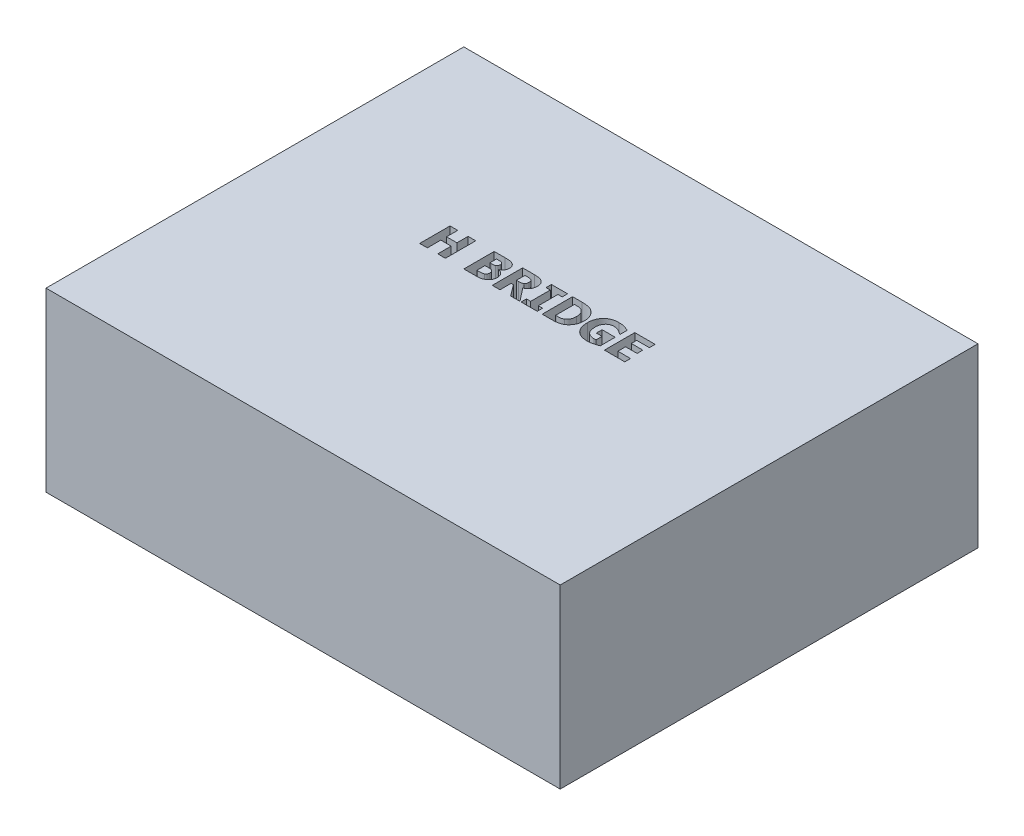
SolidWorks part; units mm, degrees
ref_plane "Front Plane" through (0, 0, 0) normal (0, 0, 1) x (1, 0, 0)
ref_plane "Top Plane" through (0, 0, 0) normal (0, 1, 0) x (1, 0, 0)
ref_plane "Right Plane" through (0, 0, 0) normal (1, 0, 0) x (0, 0, -1)
sketch "Sketch1" plane through (0, 0, 0) normal (0, 1, 0) x (1, 0, 0)
  line L1 (32, -26) -> (-32, -26)
  line L2 (32, -26) -> (32, 26)
  line L3 (32, 26) -> (-32, 26)
  line L4 (-32, -26) -> (-32, 26)
  line L5 (32, -26) -> (-32, 26) construction
  line L6 (32, 26) -> (-32, -26) construction
  point P0 (0, 0)
  dimension "D1" = 64
  dimension "D2" = 52
extrude "Boss-Extrude1" add sketch "Sketch1" along normal blind 22
sketch "Sketch2" plane through (0, 22, 0) normal (0, 1, 0) x (1, 0, 0)
  text T0 "H BRIDGE" font "Tahoma" height in points 14
extrude "Cut-Extrude1" cut sketch "Sketch2" against normal blind 5
